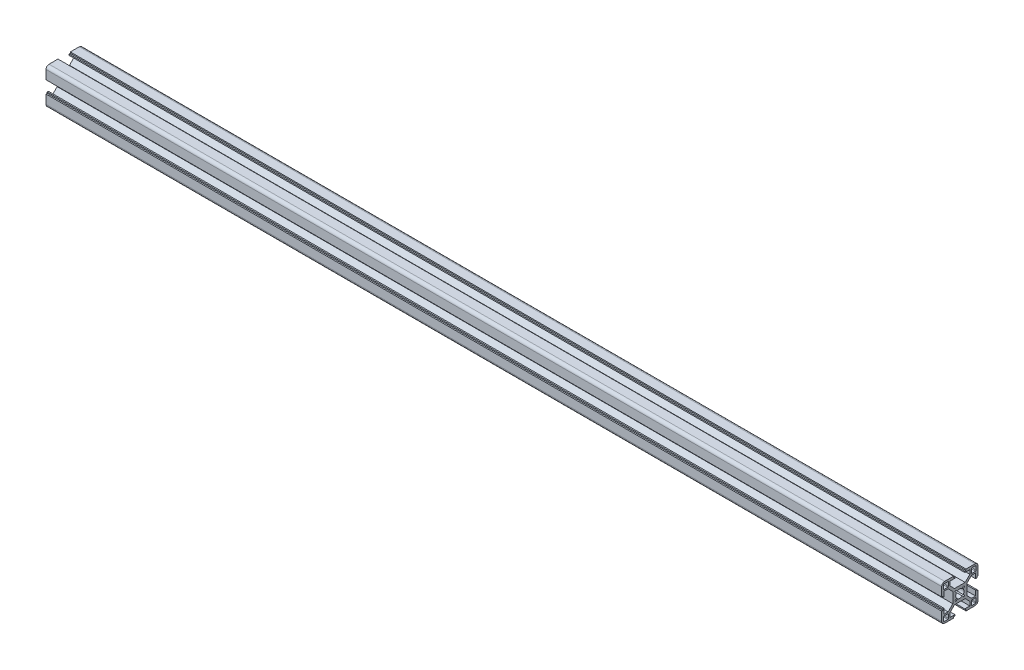
SolidWorks part; units mm, degrees
ref_plane "前视基准面" through (0, 0, 0) normal (0, 0, 1) x (1, 0, 0)
ref_plane "上视基准面" through (0, 0, 0) normal (0, 1, 0) x (1, 0, 0)
ref_plane "右视基准面" through (0, 0, 0) normal (1, 0, 0) x (0, 0, -1)
other "Configuration Table"
sketch "草图1" plane through (0, 0, 0) normal (1, 0, 0) x (0, 0, -1)
  line L0 (-5.1496, -13.7047) -> (-4.1496, -13.7047)
  line L1 (-4.1496, -13.7047) -> (-4.1496, -12.7047)
  line L2 (-4.1496, -12.7047) -> (-8.2996, -12.7047)
  line L3 (-8.2996, -12.7047) -> (-8.2996, -9.3689)
  line L4 (-8.2996, -9.3689) -> (-4.4354, -5.5047)
  line L5 (-4.4354, -5.5047) -> (4.3362, -5.5047)
  line L6 (4.3362, -5.5047) -> (8.2004, -9.3689)
  line L7 (8.2004, -9.3689) -> (8.2004, -12.7047)
  line L8 (8.2004, -12.7047) -> (4.0504, -12.7047)
  line L9 (4.0504, -12.7047) -> (4.0504, -13.7047)
  line L10 (4.0504, -13.7047) -> (5.0504, -13.7047)
  line L11 (5.0504, -13.7047) -> (5.0504, -14.7047)
  line L12 (5.0504, -14.7047) -> (12.4504, -14.7047)
  line L13 (14.9504, -12.2047) -> (14.9504, -4.8047)
  line L14 (14.9504, -4.8047) -> (13.9504, -4.8047)
  line L15 (13.9504, -4.8047) -> (13.9504, -3.8047)
  line L16 (13.9504, -3.8047) -> (12.9504, -3.8047)
  line L17 (12.9504, -3.8047) -> (12.9504, -7.9547)
  line L18 (12.9504, -7.9547) -> (9.6146, -7.9547)
  line L19 (9.6146, -7.9547) -> (5.7504, -4.0905)
  line L20 (5.7504, -4.0905) -> (5.7504, 4.6811)
  line L21 (5.7504, 4.6811) -> (9.6146, 8.5453)
  line L22 (9.6146, 8.5453) -> (12.9504, 8.5453)
  line L23 (12.9504, 8.5453) -> (12.9504, 4.3953)
  line L24 (12.9504, 4.3953) -> (13.9504, 4.3953)
  line L25 (13.9504, 4.3953) -> (13.9504, 5.3953)
  line L26 (13.9504, 5.3953) -> (14.9504, 5.3953)
  line L27 (14.9504, 5.3953) -> (14.9504, 12.7953)
  line L28 (12.4504, 15.2953) -> (5.0504, 15.2953)
  line L29 (5.0504, 15.2953) -> (5.0504, 14.2953)
  line L30 (5.0504, 14.2953) -> (4.0504, 14.2953)
  line L31 (4.0504, 14.2953) -> (4.0504, 13.2953)
  line L32 (4.0504, 13.2953) -> (8.2004, 13.2953)
  line L33 (8.2004, 13.2953) -> (8.2004, 9.9595)
  line L34 (8.2004, 9.9595) -> (4.3362, 6.0953)
  line L35 (4.3362, 6.0953) -> (-4.4354, 6.0953)
  line L36 (-4.4354, 6.0953) -> (-8.2996, 9.9595)
  line L37 (-8.2996, 9.9595) -> (-8.2996, 13.2953)
  line L38 (-8.2996, 13.2953) -> (-4.1496, 13.2953)
  line L39 (-4.1496, 13.2953) -> (-4.1496, 14.2953)
  line L40 (-4.1496, 14.2953) -> (-5.1496, 14.2953)
  line L41 (-5.1496, 14.2953) -> (-5.1496, 15.2953)
  line L42 (-5.1496, 15.2953) -> (-12.5496, 15.2953)
  line L43 (-15.0496, 12.7953) -> (-15.0496, 5.3953)
  line L44 (-15.0496, 5.3953) -> (-14.0496, 5.3953)
  line L45 (-14.0496, 5.3953) -> (-14.0496, 4.3953)
  line L46 (-14.0496, 4.3953) -> (-13.0496, 4.3953)
  line L47 (-13.0496, 4.3953) -> (-13.0496, 8.5453)
  line L48 (-13.0496, 8.5453) -> (-9.7138, 8.5453)
  line L49 (-9.7138, 8.5453) -> (-5.8496, 4.6811)
  line L50 (-5.8496, 4.6811) -> (-5.8496, -4.0905)
  line L51 (-5.8496, -4.0905) -> (-9.7138, -7.9547)
  line L52 (-9.7138, -7.9547) -> (-13.0496, -7.9547)
  line L53 (-13.0496, -7.9547) -> (-13.0496, -3.8047)
  line L54 (-13.0496, -3.8047) -> (-14.0496, -3.8047)
  line L55 (-14.0496, -3.8047) -> (-14.0496, -4.8047)
  line L56 (-14.0496, -4.8047) -> (-15.0496, -4.8047)
  line L57 (-15.0496, -4.8047) -> (-15.0496, -12.2047)
  line L58 (-12.5496, -14.7047) -> (-5.1496, -14.7047)
  line L59 (-5.1496, -14.7047) -> (-5.1496, -13.7047)
  line L60 (-10.0496, 9.7953) -> (-13.0496, 9.7953)
  line L61 (-13.5496, 10.2953) -> (-13.5496, 13.2953)
  line L62 (-13.0496, 13.7953) -> (-10.0496, 13.7953)
  line L63 (-9.5496, 13.2953) -> (-9.5496, 10.2953)
  line L64 (-10.0496, -13.2047) -> (-13.0496, -13.2047)
  line L65 (-13.5496, -12.7047) -> (-13.5496, -9.7047)
  line L66 (-13.0496, -9.2047) -> (-10.0496, -9.2047)
  line L67 (-9.5496, -9.7047) -> (-9.5496, -12.7047)
  line L68 (12.9504, 9.7953) -> (9.9504, 9.7953)
  line L69 (9.4504, 10.2953) -> (9.4504, 13.2953)
  line L70 (9.9504, 13.7953) -> (12.9504, 13.7953)
  line L71 (13.4504, 13.2953) -> (13.4504, 10.2953)
  line L72 (13.4504, -9.7047) -> (13.4504, -12.7047)
  line L73 (12.9504, -13.2047) -> (9.9504, -13.2047)
  line L74 (9.4504, -12.7047) -> (9.4504, -9.7047)
  line L75 (9.9504, -9.2047) -> (12.9504, -9.2047)
  line L76 (-4.08, 3.6186) -> (-3.3729, 4.3257)
  line L77 (-3.3729, 4.3257) -> (-2.074, 3.0269)
  line L78 (1.9749, 3.0269) -> (3.2737, 4.3257)
  line L79 (3.2737, 4.3257) -> (3.9808, 3.6186)
  line L80 (3.9808, 3.6186) -> (2.682, 2.3198)
  line L81 (2.682, -1.7291) -> (3.9808, -3.028)
  line L82 (3.9808, -3.028) -> (3.2737, -3.7351)
  line L83 (3.2737, -3.7351) -> (1.9749, -2.4362)
  line L84 (-2.074, -2.4362) -> (-3.3729, -3.7351)
  line L85 (-3.3729, -3.7351) -> (-4.08, -3.028)
  line L86 (-4.08, -3.028) -> (-2.7811, -1.7291)
  line L87 (-2.7811, 2.3198) -> (-4.08, 3.6186)
  arc A0 (12.4504, -14.7047) -> (14.9504, -12.2047) centre (12.4504, -12.2047) ccw
  arc A1 (14.9504, 12.7953) -> (12.4504, 15.2953) centre (12.4504, 12.7953) ccw
  arc A2 (-12.5496, 15.2953) -> (-15.0496, 12.7953) centre (-12.5496, 12.7953) ccw
  arc A3 (-15.0496, -12.2047) -> (-12.5496, -14.7047) centre (-12.5496, -12.2047) ccw
  arc A4 (-9.5496, 10.2953) -> (-10.0496, 9.7953) centre (-10.0496, 10.2953) cw
  arc A5 (-13.0496, 9.7953) -> (-13.5496, 10.2953) centre (-13.0496, 10.2953) cw
  arc A6 (-13.5496, 13.2953) -> (-13.0496, 13.7953) centre (-13.0496, 13.2953) cw
  arc A7 (-10.0496, 13.7953) -> (-9.5496, 13.2953) centre (-10.0496, 13.2953) cw
  arc A8 (-9.5496, -12.7047) -> (-10.0496, -13.2047) centre (-10.0496, -12.7047) cw
  arc A9 (-13.0496, -13.2047) -> (-13.5496, -12.7047) centre (-13.0496, -12.7047) cw
  arc A10 (-13.5496, -9.7047) -> (-13.0496, -9.2047) centre (-13.0496, -9.7047) cw
  arc A11 (-10.0496, -9.2047) -> (-9.5496, -9.7047) centre (-10.0496, -9.7047) cw
  arc A12 (13.4504, 10.2953) -> (12.9504, 9.7953) centre (12.9504, 10.2953) cw
  arc A13 (9.9504, 9.7953) -> (9.4504, 10.2953) centre (9.9504, 10.2953) cw
  arc A14 (9.4504, 13.2953) -> (9.9504, 13.7953) centre (9.9504, 13.2953) cw
  arc A15 (12.9504, 13.7953) -> (13.4504, 13.2953) centre (12.9504, 13.2953) cw
  arc A16 (12.9504, -9.2047) -> (13.4504, -9.7047) centre (12.9504, -9.7047) cw
  arc A17 (13.4504, -12.7047) -> (12.9504, -13.2047) centre (12.9504, -12.7047) cw
  arc A18 (9.9504, -13.2047) -> (9.4504, -12.7047) centre (9.9504, -12.7047) cw
  arc A19 (9.4504, -9.7047) -> (9.9504, -9.2047) centre (9.9504, -9.7047) cw
  arc A20 (-2.074, 3.0269) -> (1.9749, 3.0269) centre (-0.0496, 0.2953) cw
  arc A21 (2.682, 2.3198) -> (2.682, -1.7291) centre (-0.0496, 0.2953) cw
  arc A22 (1.9749, -2.4362) -> (-2.074, -2.4362) centre (-0.0496, 0.2953) cw
  arc A23 (-2.7811, -1.7291) -> (-2.7811, 2.3198) centre (-0.0496, 0.2953) cw
extrude "凸台-拉伸1" add sketch "草图1" against normal blind 50
sketch "草图2" plane through (0, 0, 0) normal (1, 0, 0) x (0, 0, -1)
  line L4 (-13.0496, 9.7953) -> (-10.0496, 9.7953)
  line L5 (-13.5496, 13.2953) -> (-13.5496, 10.2953)
  line L6 (-10.0496, 13.7953) -> (-13.0496, 13.7953)
  line L7 (-9.5496, 10.2953) -> (-9.5496, 13.2953)
  line L8 (-13.0496, 9.7953) -> (-10.0496, 9.7953)
  line L9 (-13.5496, 13.2953) -> (-13.5496, 10.2953)
  line L10 (-10.0496, 13.7953) -> (-13.0496, 13.7953)
  line L11 (-9.5496, 10.2953) -> (-9.5496, 13.2953)
  line L12 (-13.0496, -13.2047) -> (-10.0496, -13.2047)
  line L13 (-13.5496, -9.7047) -> (-13.5496, -12.7047)
  line L14 (-10.0496, -9.2047) -> (-13.0496, -9.2047)
  line L15 (-9.5496, -12.7047) -> (-9.5496, -9.7047)
  line L16 (-13.0496, -13.2047) -> (-10.0496, -13.2047)
  line L17 (-13.5496, -9.7047) -> (-13.5496, -12.7047)
  line L18 (-10.0496, -9.2047) -> (-13.0496, -9.2047)
  line L19 (-9.5496, -12.7047) -> (-9.5496, -9.7047)
  line L20 (9.4504, 13.2953) -> (9.4504, 10.2953)
  line L21 (12.9504, 13.7953) -> (9.9504, 13.7953)
  line L22 (13.4504, 10.2953) -> (13.4504, 13.2953)
  line L23 (9.9504, 9.7953) -> (12.9504, 9.7953)
  line L24 (9.4504, 13.2953) -> (9.4504, 10.2953)
  line L25 (12.9504, 13.7953) -> (9.9504, 13.7953)
  line L26 (13.4504, 10.2953) -> (13.4504, 13.2953)
  line L27 (9.9504, 9.7953) -> (12.9504, 9.7953)
  line L28 (9.4504, -9.7047) -> (9.4504, -12.7047)
  line L29 (12.9504, -9.2047) -> (9.9504, -9.2047)
  line L30 (13.4504, -12.7047) -> (13.4504, -9.7047)
  line L31 (9.9504, -13.2047) -> (12.9504, -13.2047)
  line L32 (9.4504, -9.7047) -> (9.4504, -12.7047)
  line L33 (12.9504, -9.2047) -> (9.9504, -9.2047)
  line L34 (13.4504, -12.7047) -> (13.4504, -9.7047)
  line L35 (9.9504, -13.2047) -> (12.9504, -13.2047)
  line L44 (-3.3729, -3.7351) -> (-2.074, -2.4362)
  line L45 (-4.08, -3.028) -> (-3.3729, -3.7351)
  line L46 (-2.7811, -1.7291) -> (-4.08, -3.028)
  line L47 (-4.08, 3.6186) -> (-2.7811, 2.3198)
  line L48 (-3.3729, 4.3257) -> (-4.08, 3.6186)
  line L49 (-2.074, 3.0269) -> (-3.3729, 4.3257)
  line L50 (3.2737, 4.3257) -> (1.9749, 3.0269)
  line L51 (3.9808, 3.6186) -> (3.2737, 4.3257)
  line L52 (2.682, 2.3198) -> (3.9808, 3.6186)
  line L53 (3.9808, -3.028) -> (2.682, -1.7291)
  line L54 (3.2737, -3.7351) -> (3.9808, -3.028)
  line L55 (1.9749, -2.4362) -> (3.2737, -3.7351)
  line L56 (-3.3729, -3.7351) -> (-2.074, -2.4362)
  line L57 (-4.08, -3.028) -> (-3.3729, -3.7351)
  line L58 (-2.7811, -1.7291) -> (-4.08, -3.028)
  line L59 (-4.08, 3.6186) -> (-2.7811, 2.3198)
  line L60 (-3.3729, 4.3257) -> (-4.08, 3.6186)
  line L61 (-2.074, 3.0269) -> (-3.3729, 4.3257)
  line L62 (3.2737, 4.3257) -> (1.9749, 3.0269)
  line L63 (3.9808, 3.6186) -> (3.2737, 4.3257)
  line L64 (2.682, 2.3198) -> (3.9808, 3.6186)
  line L65 (3.9808, -3.028) -> (2.682, -1.7291)
  line L66 (3.2737, -3.7351) -> (3.9808, -3.028)
  line L67 (1.9749, -2.4362) -> (3.2737, -3.7351)
  line L68 (-15.0496, -4.8047) -> (-15.0496, -12.2047)
  line L69 (-14.0496, -4.8047) -> (-15.0496, -4.8047)
  line L70 (-14.0496, -3.8047) -> (-14.0496, -4.8047)
  line L71 (-13.0496, -3.8047) -> (-14.0496, -3.8047)
  line L72 (-13.0496, -7.9547) -> (-13.0496, -3.8047)
  line L73 (-9.7138, -7.9547) -> (-13.0496, -7.9547)
  line L74 (-5.8496, -4.0905) -> (-9.7138, -7.9547)
  line L75 (-5.8496, 4.6811) -> (-5.8496, -4.0905)
  line L76 (-9.7138, 8.5453) -> (-5.8496, 4.6811)
  line L77 (-13.0496, 8.5453) -> (-9.7138, 8.5453)
  line L78 (-13.0496, 4.3953) -> (-13.0496, 8.5453)
  line L79 (-14.0496, 4.3953) -> (-13.0496, 4.3953)
  line L80 (-14.0496, 5.3953) -> (-14.0496, 4.3953)
  line L81 (-15.0496, 5.3953) -> (-14.0496, 5.3953)
  line L82 (-15.0496, 12.7953) -> (-15.0496, 5.3953)
  line L83 (-5.1496, 15.2953) -> (-12.5496, 15.2953)
  line L84 (-5.1496, 14.2953) -> (-5.1496, 15.2953)
  line L85 (-4.1496, 14.2953) -> (-5.1496, 14.2953)
  line L86 (-4.1496, 13.2953) -> (-4.1496, 14.2953)
  line L87 (-8.2996, 13.2953) -> (-4.1496, 13.2953)
  line L88 (-8.2996, 9.9595) -> (-8.2996, 13.2953)
  line L89 (-4.4354, 6.0953) -> (-8.2996, 9.9595)
  line L90 (4.3362, 6.0953) -> (-4.4354, 6.0953)
  line L91 (8.2004, 9.9595) -> (4.3362, 6.0953)
  line L92 (8.2004, 13.2953) -> (8.2004, 9.9595)
  line L93 (4.0504, 13.2953) -> (8.2004, 13.2953)
  line L94 (4.0504, 14.2953) -> (4.0504, 13.2953)
  line L95 (5.0504, 14.2953) -> (4.0504, 14.2953)
  line L96 (5.0504, 15.2953) -> (5.0504, 14.2953)
  line L97 (12.4504, 15.2953) -> (5.0504, 15.2953)
  line L98 (14.9504, 5.3953) -> (14.9504, 12.7953)
  line L99 (13.9504, 5.3953) -> (14.9504, 5.3953)
  line L100 (13.9504, 4.3953) -> (13.9504, 5.3953)
  line L101 (12.9504, 4.3953) -> (13.9504, 4.3953)
  line L102 (12.9504, 8.5453) -> (12.9504, 4.3953)
  line L103 (9.6146, 8.5453) -> (12.9504, 8.5453)
  line L104 (5.7504, 4.6811) -> (9.6146, 8.5453)
  line L105 (5.7504, -4.0905) -> (5.7504, 4.6811)
  line L106 (9.6146, -7.9547) -> (5.7504, -4.0905)
  line L107 (12.9504, -7.9547) -> (9.6146, -7.9547)
  line L108 (12.9504, -3.8047) -> (12.9504, -7.9547)
  line L109 (13.9504, -3.8047) -> (12.9504, -3.8047)
  line L110 (13.9504, -4.8047) -> (13.9504, -3.8047)
  line L111 (14.9504, -4.8047) -> (13.9504, -4.8047)
  line L112 (14.9504, -12.2047) -> (14.9504, -4.8047)
  line L113 (5.0504, -14.7047) -> (12.4504, -14.7047)
  line L114 (5.0504, -13.7047) -> (5.0504, -14.7047)
  line L115 (4.0504, -13.7047) -> (5.0504, -13.7047)
  line L116 (4.0504, -12.7047) -> (4.0504, -13.7047)
  line L117 (8.2004, -12.7047) -> (4.0504, -12.7047)
  line L118 (8.2004, -9.3689) -> (8.2004, -12.7047)
  line L119 (4.3362, -5.5047) -> (8.2004, -9.3689)
  line L120 (-4.4354, -5.5047) -> (4.3362, -5.5047)
  line L121 (-8.2996, -9.3689) -> (-4.4354, -5.5047)
  line L122 (-8.2996, -12.7047) -> (-8.2996, -9.3689)
  line L123 (-4.1496, -12.7047) -> (-8.2996, -12.7047)
  line L124 (-4.1496, -13.7047) -> (-4.1496, -12.7047)
  line L125 (-5.1496, -13.7047) -> (-4.1496, -13.7047)
  line L126 (-5.1496, -14.7047) -> (-5.1496, -13.7047)
  line L127 (-12.5496, -14.7047) -> (-5.1496, -14.7047)
  line L128 (-15.0496, -4.8047) -> (-15.0496, -12.2047)
  line L129 (-14.0496, -4.8047) -> (-15.0496, -4.8047)
  line L130 (-14.0496, -3.8047) -> (-14.0496, -4.8047)
  line L131 (-13.0496, -3.8047) -> (-14.0496, -3.8047)
  line L132 (-13.0496, -7.9547) -> (-13.0496, -3.8047)
  line L133 (-9.7138, -7.9547) -> (-13.0496, -7.9547)
  line L134 (-5.8496, -4.0905) -> (-9.7138, -7.9547)
  line L135 (-5.8496, 4.6811) -> (-5.8496, -4.0905)
  line L136 (-9.7138, 8.5453) -> (-5.8496, 4.6811)
  line L137 (-13.0496, 8.5453) -> (-9.7138, 8.5453)
  line L138 (-13.0496, 4.3953) -> (-13.0496, 8.5453)
  line L139 (-14.0496, 4.3953) -> (-13.0496, 4.3953)
  line L140 (-14.0496, 5.3953) -> (-14.0496, 4.3953)
  line L141 (-15.0496, 5.3953) -> (-14.0496, 5.3953)
  line L142 (-15.0496, 12.7953) -> (-15.0496, 5.3953)
  line L143 (-5.1496, 15.2953) -> (-12.5496, 15.2953)
  line L144 (-5.1496, 14.2953) -> (-5.1496, 15.2953)
  line L145 (-4.1496, 14.2953) -> (-5.1496, 14.2953)
  line L146 (-4.1496, 13.2953) -> (-4.1496, 14.2953)
  line L147 (-8.2996, 13.2953) -> (-4.1496, 13.2953)
  line L148 (-8.2996, 9.9595) -> (-8.2996, 13.2953)
  line L149 (-4.4354, 6.0953) -> (-8.2996, 9.9595)
  line L150 (4.3362, 6.0953) -> (-4.4354, 6.0953)
  line L151 (8.2004, 9.9595) -> (4.3362, 6.0953)
  line L152 (8.2004, 13.2953) -> (8.2004, 9.9595)
  line L153 (4.0504, 13.2953) -> (8.2004, 13.2953)
  line L154 (4.0504, 14.2953) -> (4.0504, 13.2953)
  line L155 (5.0504, 14.2953) -> (4.0504, 14.2953)
  line L156 (5.0504, 15.2953) -> (5.0504, 14.2953)
  line L157 (12.4504, 15.2953) -> (5.0504, 15.2953)
  line L158 (14.9504, 5.3953) -> (14.9504, 12.7953)
  line L159 (13.9504, 5.3953) -> (14.9504, 5.3953)
  line L160 (13.9504, 4.3953) -> (13.9504, 5.3953)
  line L161 (12.9504, 4.3953) -> (13.9504, 4.3953)
  line L162 (12.9504, 8.5453) -> (12.9504, 4.3953)
  line L163 (9.6146, 8.5453) -> (12.9504, 8.5453)
  line L164 (5.7504, 4.6811) -> (9.6146, 8.5453)
  line L165 (5.7504, -4.0905) -> (5.7504, 4.6811)
  line L166 (9.6146, -7.9547) -> (5.7504, -4.0905)
  line L167 (12.9504, -7.9547) -> (9.6146, -7.9547)
  line L168 (12.9504, -3.8047) -> (12.9504, -7.9547)
  line L169 (13.9504, -3.8047) -> (12.9504, -3.8047)
  line L170 (13.9504, -4.8047) -> (13.9504, -3.8047)
  line L171 (14.9504, -4.8047) -> (13.9504, -4.8047)
  line L172 (14.9504, -12.2047) -> (14.9504, -4.8047)
  line L173 (5.0504, -14.7047) -> (12.4504, -14.7047)
  line L174 (5.0504, -13.7047) -> (5.0504, -14.7047)
  line L175 (4.0504, -13.7047) -> (5.0504, -13.7047)
  line L176 (4.0504, -12.7047) -> (4.0504, -13.7047)
  line L177 (8.2004, -12.7047) -> (4.0504, -12.7047)
  line L178 (8.2004, -9.3689) -> (8.2004, -12.7047)
  line L179 (4.3362, -5.5047) -> (8.2004, -9.3689)
  line L180 (-4.4354, -5.5047) -> (4.3362, -5.5047)
  line L181 (-8.2996, -9.3689) -> (-4.4354, -5.5047)
  line L182 (-8.2996, -12.7047) -> (-8.2996, -9.3689)
  line L183 (-4.1496, -12.7047) -> (-8.2996, -12.7047)
  line L184 (-4.1496, -13.7047) -> (-4.1496, -12.7047)
  line L185 (-5.1496, -13.7047) -> (-4.1496, -13.7047)
  line L186 (-5.1496, -14.7047) -> (-5.1496, -13.7047)
  line L187 (-12.5496, -14.7047) -> (-5.1496, -14.7047)
  arc A4 (-13.5496, 10.2953) -> (-13.0496, 9.7953) centre (-13.0496, 10.2953) ccw
  arc A5 (-13.0496, 13.7953) -> (-13.5496, 13.2953) centre (-13.0496, 13.2953) ccw
  arc A6 (-9.5496, 13.2953) -> (-10.0496, 13.7953) centre (-10.0496, 13.2953) ccw
  arc A7 (-10.0496, 9.7953) -> (-9.5496, 10.2953) centre (-10.0496, 10.2953) ccw
  arc A8 (-13.5496, 10.2953) -> (-13.0496, 9.7953) centre (-13.0496, 10.2953) ccw
  arc A9 (-13.0496, 13.7953) -> (-13.5496, 13.2953) centre (-13.0496, 13.2953) ccw
  arc A10 (-9.5496, 13.2953) -> (-10.0496, 13.7953) centre (-10.0496, 13.2953) ccw
  arc A11 (-10.0496, 9.7953) -> (-9.5496, 10.2953) centre (-10.0496, 10.2953) ccw
  arc A12 (-12.5496, 15.2953) -> (-15.0496, 12.7953) centre (-12.5496, 12.7953) ccw
  arc A13 (14.9504, 12.7953) -> (12.4504, 15.2953) centre (12.4504, 12.7953) ccw
  arc A14 (12.4504, -14.7047) -> (14.9504, -12.2047) centre (12.4504, -12.2047) ccw
  arc A15 (-15.0496, -12.2047) -> (-12.5496, -14.7047) centre (-12.5496, -12.2047) ccw
  arc A16 (-12.5496, 15.2953) -> (-15.0496, 12.7953) centre (-12.5496, 12.7953) ccw
  arc A17 (14.9504, 12.7953) -> (12.4504, 15.2953) centre (12.4504, 12.7953) ccw
  arc A18 (12.4504, -14.7047) -> (14.9504, -12.2047) centre (12.4504, -12.2047) ccw
  arc A19 (-15.0496, -12.2047) -> (-12.5496, -14.7047) centre (-12.5496, -12.2047) ccw
  arc A20 (-13.5496, -12.7047) -> (-13.0496, -13.2047) centre (-13.0496, -12.7047) ccw
  arc A21 (-13.0496, -9.2047) -> (-13.5496, -9.7047) centre (-13.0496, -9.7047) ccw
  arc A22 (-9.5496, -9.7047) -> (-10.0496, -9.2047) centre (-10.0496, -9.7047) ccw
  arc A23 (-10.0496, -13.2047) -> (-9.5496, -12.7047) centre (-10.0496, -12.7047) ccw
  arc A24 (-13.5496, -12.7047) -> (-13.0496, -13.2047) centre (-13.0496, -12.7047) ccw
  arc A25 (-13.0496, -9.2047) -> (-13.5496, -9.7047) centre (-13.0496, -9.7047) ccw
  arc A26 (-9.5496, -9.7047) -> (-10.0496, -9.2047) centre (-10.0496, -9.7047) ccw
  arc A27 (-10.0496, -13.2047) -> (-9.5496, -12.7047) centre (-10.0496, -12.7047) ccw
  arc A28 (9.9504, 13.7953) -> (9.4504, 13.2953) centre (9.9504, 13.2953) ccw
  arc A29 (13.4504, 13.2953) -> (12.9504, 13.7953) centre (12.9504, 13.2953) ccw
  arc A30 (12.9504, 9.7953) -> (13.4504, 10.2953) centre (12.9504, 10.2953) ccw
  arc A31 (9.4504, 10.2953) -> (9.9504, 9.7953) centre (9.9504, 10.2953) ccw
  arc A32 (9.9504, 13.7953) -> (9.4504, 13.2953) centre (9.9504, 13.2953) ccw
  arc A33 (13.4504, 13.2953) -> (12.9504, 13.7953) centre (12.9504, 13.2953) ccw
  arc A34 (12.9504, 9.7953) -> (13.4504, 10.2953) centre (12.9504, 10.2953) ccw
  arc A35 (9.4504, 10.2953) -> (9.9504, 9.7953) centre (9.9504, 10.2953) ccw
  arc A36 (9.9504, -9.2047) -> (9.4504, -9.7047) centre (9.9504, -9.7047) ccw
  arc A37 (13.4504, -9.7047) -> (12.9504, -9.2047) centre (12.9504, -9.7047) ccw
  arc A38 (12.9504, -13.2047) -> (13.4504, -12.7047) centre (12.9504, -12.7047) ccw
  arc A39 (9.4504, -12.7047) -> (9.9504, -13.2047) centre (9.9504, -12.7047) ccw
  arc A40 (9.9504, -9.2047) -> (9.4504, -9.7047) centre (9.9504, -9.7047) ccw
  arc A41 (13.4504, -9.7047) -> (12.9504, -9.2047) centre (12.9504, -9.7047) ccw
  arc A42 (12.9504, -13.2047) -> (13.4504, -12.7047) centre (12.9504, -12.7047) ccw
  arc A43 (9.4504, -12.7047) -> (9.9504, -13.2047) centre (9.9504, -12.7047) ccw
  arc A44 (-2.7811, 2.3198) -> (-2.7811, -1.7291) centre (-0.0496, 0.2953) ccw
  arc A45 (1.9749, 3.0269) -> (-2.074, 3.0269) centre (-0.0496, 0.2953) ccw
  arc A46 (2.682, -1.7291) -> (2.682, 2.3198) centre (-0.0496, 0.2953) ccw
  arc A47 (-2.074, -2.4362) -> (1.9749, -2.4362) centre (-0.0496, 0.2953) ccw
  arc A48 (-2.7811, 2.3198) -> (-2.7811, -1.7291) centre (-0.0496, 0.2953) ccw
  arc A49 (1.9749, 3.0269) -> (-2.074, 3.0269) centre (-0.0496, 0.2953) ccw
  arc A50 (2.682, -1.7291) -> (2.682, 2.3198) centre (-0.0496, 0.2953) ccw
  arc A51 (-2.074, -2.4362) -> (1.9749, -2.4362) centre (-0.0496, 0.2953) ccw
  dimension "D1" = 0
  dimension "D2" = 0
  dimension "D3" = 0
  dimension "D4" = 0
  dimension "D5" = 0
  dimension "D6" = 0
extrude "凸台-拉伸2" add sketch "草图2" against normal blind 740
sketch "草图4" plane through (0, 0, 0) normal (0, 0, 1) x (1, 0, 0)
  line L0 (-1000, 0) -> (49000, 0) construction
  line L1 (-370, -1000) -> (-370, 49000) construction
  line L2 (-740, 4.6811) -> (-740, -4.0905) construction
  circle A0 centre (-726.5, 0) radius 3
  circle A1 centre (-13.5, 0) radius 3
  dimension "D2" = 6
  dimension "D1" = 370
  dimension "D3" = 13.5
extrude "切除-拉伸1" cut sketch "草图4" against normal up to surface (30 mm away) from surface at 15.0496 up to face at (-370, -8.5047, -14.9504) starting at face at (-370, -8.5047, 15.0496)
